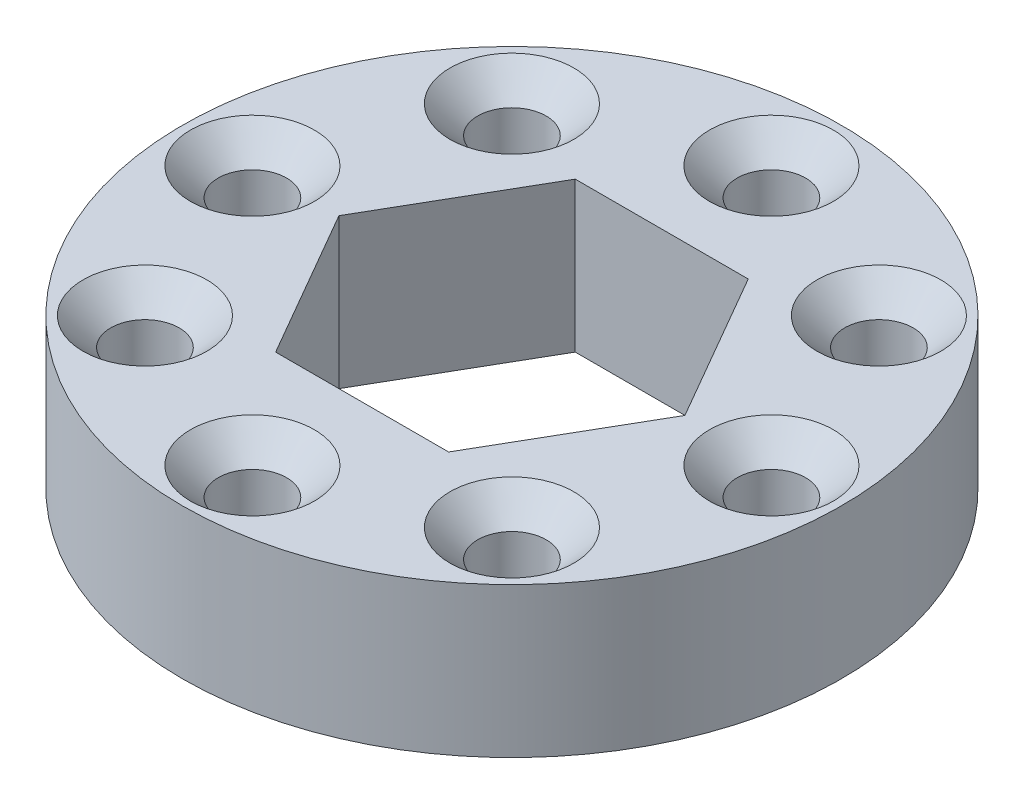
SolidWorks part; units mm, degrees
ref_plane "Front Plane" through (0, 0, 0) normal (0, 0, 1) x (1, 0, 0)
ref_plane "Top Plane" through (0, 0, 0) normal (0, 1, 0) x (1, 0, 0)
ref_plane "Right Plane" through (0, 0, 0) normal (1, 0, 0) x (0, 0, -1)
sketch "Sketch1" plane through (0, 0, 0) normal (0, 1, 0) x (1, 0, 0)
  line L1 (3.6662, 6.35) -> (-3.6662, 6.35)
  line L2 (-3.6662, 6.35) -> (-7.3323, 0)
  line L3 (-7.3323, 0) -> (-3.6662, -6.35)
  line L4 (-3.6662, -6.35) -> (3.6662, -6.35)
  line L5 (3.6662, -6.35) -> (7.3323, 0)
  line L6 (7.3323, 0) -> (3.6662, 6.35)
  circle A0 centre (0, 0) radius 13.97
  circle A1 centre (0, 0) radius 6.35 construction
  dimension "D1" = 27.94
  dimension "D2" = 12.7
extrude "Boss-Extrude1" add sketch "Sketch1" along normal mid plane 6.35
hole_wizard "M2.5 Clearance Hole1" positions "Sketch2" profile "Sketch3" hole size "M2.5" standard "ANSI Metric" end condition through all
sketch "Sketch2" plane through (0, 3.175, 0) normal (0, 1, 0) x (1, 0, 0)
  point P0 (0, 11)
  dimension "D1" = 11
sketch "Sketch3" plane through (0, 3.175, -11) normal (1, 0, 0) x (0, 0, 1)
  line L0 (0, 0) -> (0, 6.35)
  line L1 (0, 6.35) -> (1.45, 6.35)
  line L2 (1.45, 6.35) -> (1.45, 1.175)
  line L3 (1.45, 1.175) -> (2.625, 0)
  line L5 (2.625, 0) -> (0, 0)
  line L6 (-1.45, 1.175) -> (-2.625, 0) construction
  line L11 (0, -6.35) -> (0, 107.95) construction
  dimension "Thru Hole Dia." = 2.9
  dimension "Thru Hole Depth" = 6.35
  dimension "Near C'Sink Dia." = 5.25
  dimension "Near C'Sink Angle" = 90
pattern_circular "CirPattern1" count 8 over 360 about axis through (0, 0, 0) along (0, 1, 0) of "M2.5 Clearance Hole1"
